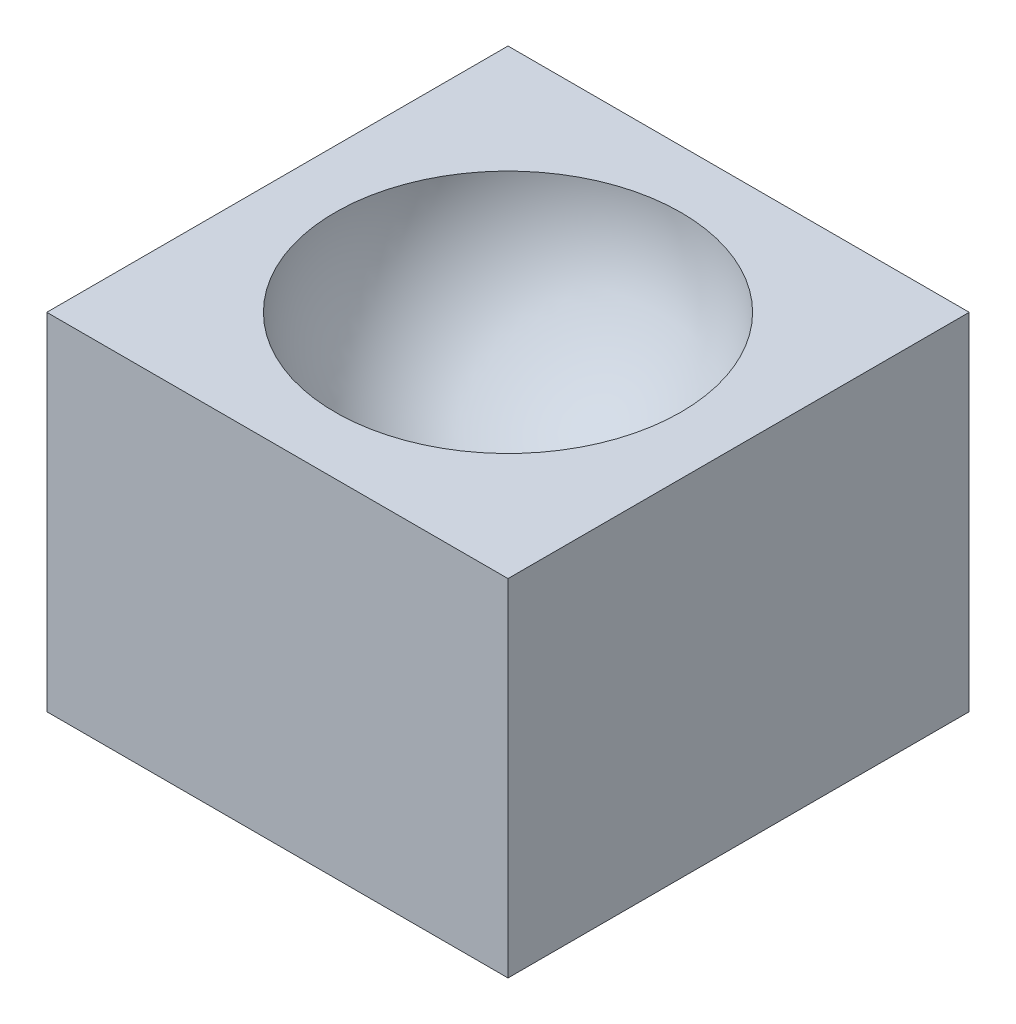
SolidWorks part; units mm, degrees
ref_plane "Front Plane" through (0, 0, 0) normal (0, 0, 1) x (1, 0, 0)
ref_plane "Top Plane" through (0, 0, 0) normal (0, 1, 0) x (1, 0, 0)
ref_plane "Right Plane" through (0, 0, 0) normal (1, 0, 0) x (0, 0, -1)
sketch "Sketch1" plane through (0, 0, 0) normal (0, 1, 0) x (1, 0, 0)
  line L1 (0, 0) -> (20, 0)
  line L2 (0, 0) -> (0, 20)
  line L3 (0, 20) -> (20, 20)
  line L4 (20, 0) -> (20, 20)
  line L5 (0, 0) -> (20, 20) construction
  line L6 (0, 20) -> (20, 0) construction
  point P4 (10, 10)
  dimension "D1" = 20
  dimension "D2" = 20
extrude "Boss-Extrude1" add sketch "Sketch1" along normal blind 15
ref_plane "Plane1" through (0, 0, -10) normal (0, 0, 1) x (1, 0, 0)
sketch "Sketch4" plane through (0, 0, -10) normal (0, 0, 1) x (1, 0, 0)
  line L0 (0, 15) -> (20, 15) construction
  line L1 (10, 22.5) -> (10, 7.5)
  arc A0 (10, 7.5) -> (10, 22.5) centre (10, 15) ccw
  dimension "D1" = 15
revolve "Cut-Revolve7" cut sketch "Sketch4" angle 360 about L1
sketch "Sketch5" plane through (0, 0, 0) normal (0, -1, 0) x (1, 0, 0)
  line L0 (20, -20) -> (0, 0) construction
  circle A0 centre (10, -10) radius 4 construction
  circle A1 centre (10, -10) radius 4.254
  dimension "D1" = 8
  dimension "D2" = 0.254
extrude "Cut-Extrude1" cut sketch "Sketch5" against normal blind 5
